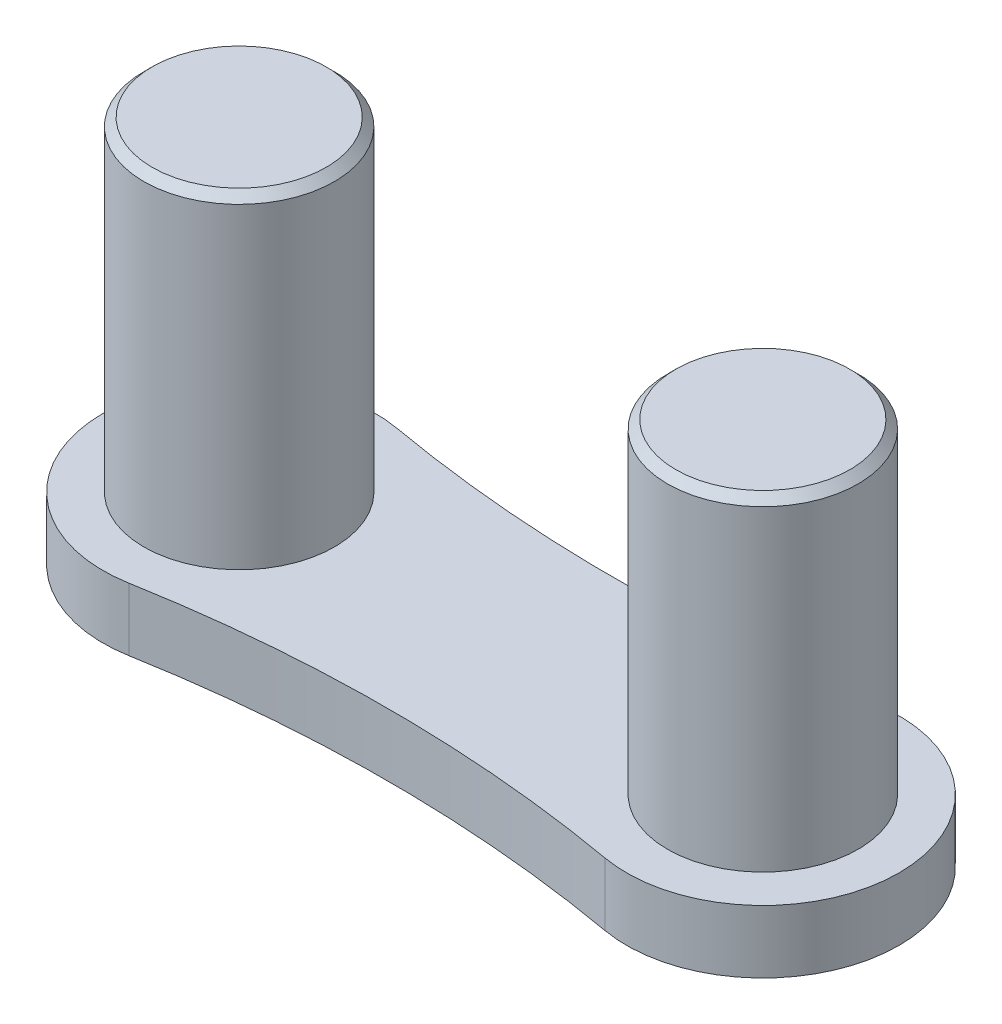
SolidWorks part; units mm, degrees
ref_plane "Front Plane" through (0, 0, 0) normal (0, 0, 1) x (1, 0, 0)
ref_plane "Top Plane" through (0, 0, 0) normal (0, 1, 0) x (1, 0, 0)
ref_plane "Right Plane" through (0, 0, 0) normal (1, 0, 0) x (0, 0, -1)
sketch "Sketch2" plane through (0, 0, 0) normal (0, 1, 0) x (1, 0, 0)
  line L0 (-3.175, 0) -> (3.175, 0) construction
  arc A0 (-2.8864, 1.6256) -> (-2.8864, -1.6256) centre (-3.175, 0) ccw
  arc A1 (2.8864, -1.6256) -> (2.8864, 1.6256) centre (3.175, 0) ccw
  arc A2 (-2.8864, 1.6256) -> (2.8864, 1.6256) centre (0, 17.8813) ccw
  arc A3 (2.8864, -1.6256) -> (-2.8864, -1.6256) centre (0, -17.8813) ccw
  point P2 (0, 0)
  dimension "D2" = 3.302
  dimension "D3" = 33.02
  dimension "D1" = 6.35
extrude "Boss-Extrude1" add sketch "Sketch2" along normal blind 0.762
sketch "Sketch3" plane through (0, 0.762, 0) normal (0, 1, 0) x (1, 0, 0)
  line L0 (-3.175, 0) -> (3.175, 0) construction
  circle A0 centre (-3.175, 0) radius 1.1557
  circle A1 centre (3.175, 0) radius 1.1557
  point P2 (0, 0)
  dimension "D1" = 6.35
  dimension "D2" = 2.3114
extrude "Boss-Extrude2" add sketch "Sketch3" along normal blind 3.937
chamfer "Chamfer1" distance 0.1 angle 45 2 edges at (3.175, 4.699, 1.1557) (-3.175, 4.699, 1.1557)
